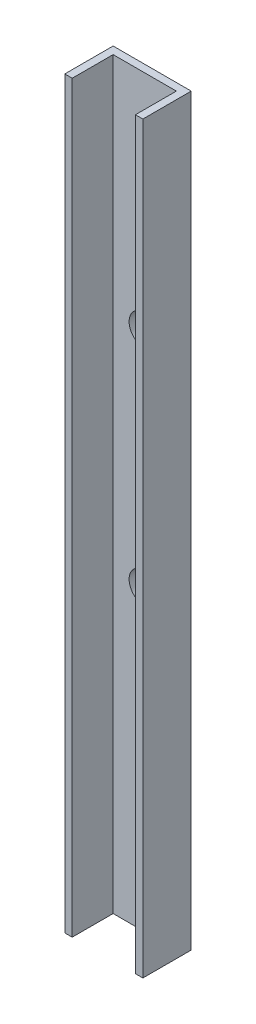
SolidWorks part; units mm, degrees
ref_plane "Front Plane" through (0, 0, 0) normal (0, 0, 1) x (1, 0, 0)
ref_plane "Top Plane" through (0, 0, 0) normal (0, 1, 0) x (1, 0, 0)
ref_plane "Right Plane" through (0, 0, 0) normal (1, 0, 0) x (0, 0, -1)
sketch "Sketch1" plane through (0, 0, 0) normal (0, 1, 0) x (1, 0, 0)
  line L0 (-3.47, -1.8133) -> (-3.47, 4.6867)
  line L1 (-3.47, 4.6867) -> (7.03, 4.6867)
  line L2 (7.03, 4.6867) -> (7.03, -1.8133)
  dimension "D1" = 10.5
  dimension "D2" = 6.5
  dimension "D3" = 6.5
extrude "Extrude-Thin1" add sketch "Sketch1" along normal blind 100 thin
sketch "Sketch2" plane through (0, 0, -4.6867) normal (0, 0, -1) x (-1, 0, 0)
  circle A0 centre (-1.78, 70) radius 2.1
  circle A1 centre (-1.78, 40) radius 2.1
extrude "Cut-Extrude1" cut sketch "Sketch2" against normal blind 10
